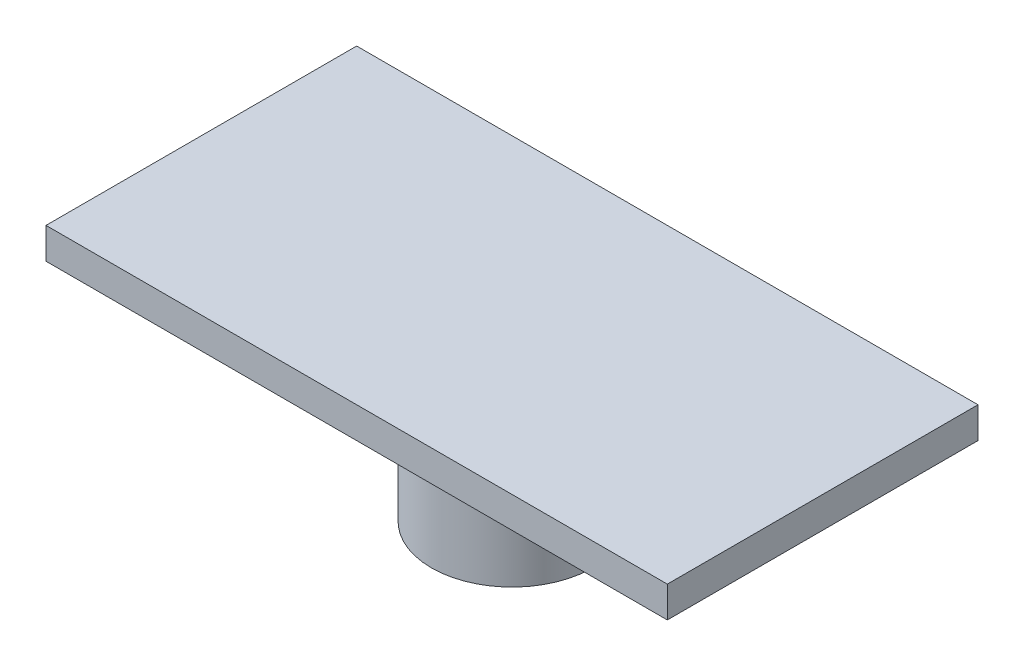
SolidWorks part; units mm, degrees
ref_plane "Front Plane" through (0, 0, 0) normal (0, 0, 1) x (1, 0, 0)
ref_plane "Top Plane" through (0, 0, 0) normal (0, 1, 0) x (1, 0, 0)
ref_plane "Right Plane" through (0, 0, 0) normal (1, 0, 0) x (0, 0, -1)
sketch "Sketch2" plane through (0, 0, 0) normal (0, 1, 0) x (1, 0, 0)
  circle A0 centre (0, 0) radius 5.1893
extrude "Boss-Extrude1" add sketch "Sketch2" along normal blind 9.5
sketch "Sketch4" plane through (0, 9.5, 0) normal (0, 1, 0) x (1, 0, 0)
  line L0 (0, 0) -> (0, 1.625)
  line L1 (0, 0) -> (0, -1.625)
  line L2 (0, 1.625) -> (2.5, 1.625)
  line L3 (0, 1.625) -> (-2.5, 1.625)
  line L4 (0, -1.625) -> (-2.5, -1.625)
  line L5 (0, -1.625) -> (2.5, -1.625)
  arc A0 (-2.5, 1.625) -> (-2.5, -1.625) centre (-0.875, 0) ccw
  arc A1 (2.5, 1.625) -> (2.5, -1.625) centre (0.875, 0) cw
extrude "Cut-Extrude1" cut sketch "Sketch4" against normal blind 11.8 contours L3 A0 L4 L1 L0 | A1 L2 L0 L1 L5
sketch "Sketch5" plane through (0, 9.5, 0) normal (0, 1, 0) x (1, 0, 0)
  line L1 (-20, 10) -> (20, 10)
  line L2 (-20, 10) -> (-20, -10)
  line L3 (-20, -10) -> (20, -10)
  line L4 (20, 10) -> (20, -10)
  line L5 (-20, 10) -> (20, -10) construction
  line L6 (-20, -10) -> (20, 10) construction
  point P0 (0, 0)
  dimension "D1" = 20
  dimension "D2" = 40
extrude "Boss-Extrude2" add sketch "Sketch5" along normal blind 2
